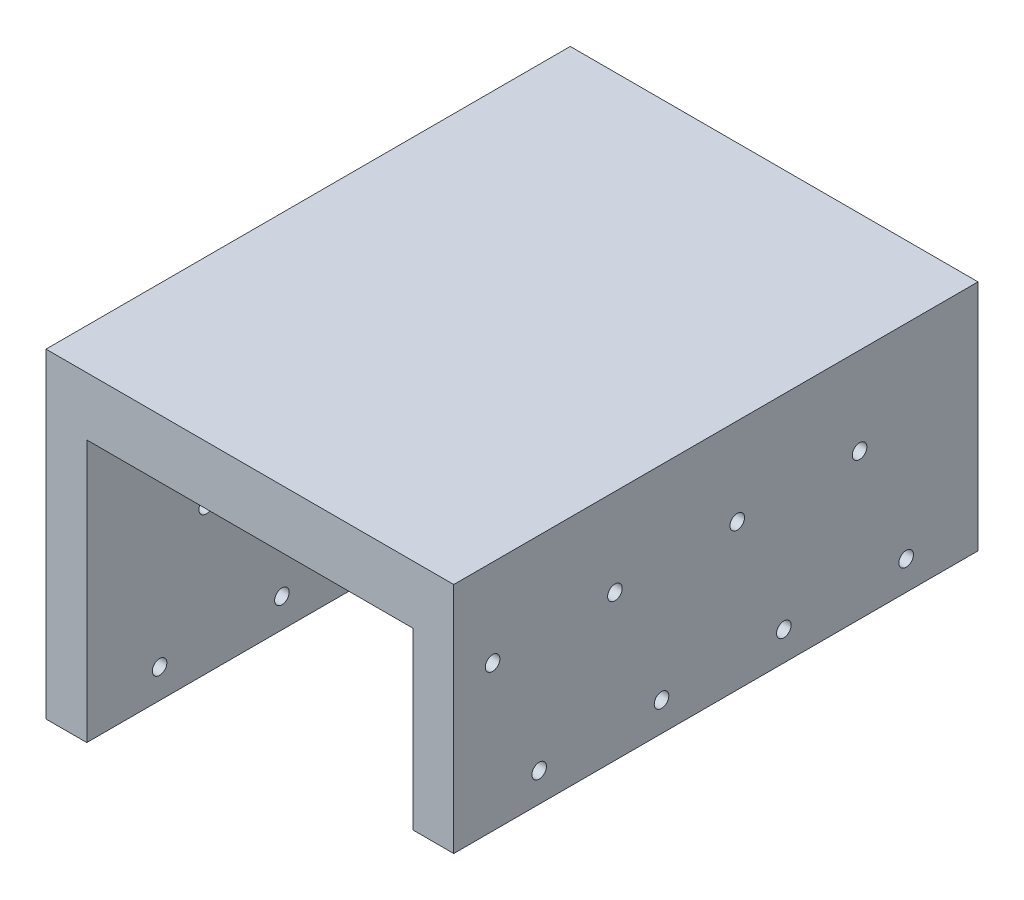
SolidWorks part; units mm, degrees
ref_plane "Front Plane" through (0, 0, 0) normal (0, 0, 1) x (1, 0, 0)
ref_plane "Top Plane" through (0, 0, 0) normal (0, 1, 0) x (1, 0, 0)
ref_plane "Right Plane" through (0, 0, 0) normal (1, 0, 0) x (0, 0, -1)
sketch "Sketch1" plane through (0, 0, 0) normal (0, 0, 1) x (1, 0, 0)
  line L1 (0, 0) -> (70, 0)
  line L2 (0, 0) -> (0, 55)
  line L3 (0, 55) -> (70, 55)
  line L4 (70, 0) -> (70, 55)
  dimension "D1" = 70
  dimension "D2" = 55
extrude "Boss-Extrude1" add sketch "Sketch1" along normal blind 90
sketch "Sketch2" plane through (0, 0, 90) normal (0, 0, 1) x (1, 0, 0)
  line L0 (7, 0) -> (7, 45)
  line L1 (0, 0) -> (70, 0) construction
  line L2 (7, 45) -> (63, 45)
  line L3 (63, 45) -> (63, 15)
  line L4 (60, 0) -> (7, 0)
  line L5 (0, 55) -> (0, 0) construction
  line L6 (70, 0) -> (70, 55) construction
  line L7 (70, 55) -> (0, 55) construction
  line L8 (63, 15) -> (70, 15)
  line L9 (70, 15) -> (70, 0)
  line L10 (70, 0) -> (60, 0)
  dimension "D1" = 7
  dimension "D2" = 7
  dimension "D3" = 10
  dimension "D4" = 15
extrude "Cut-Extrude1" cut sketch "Sketch2" against normal through all both and the other way through all
sketch "Sketch3" plane through (0, 0, 0) normal (-1, 0, 0) x (0, 0, 1)
  line L0 (90, 0) -> (0, 0) construction
  line L1 (0, 55) -> (0, 0) construction
  circle A0 centre (6.5, 25) radius 1.25
  circle A1 centre (14.5, 5) radius 1.25
  circle A2 centre (27.5, 25) radius 1.25
  circle A3 centre (35.5, 5) radius 1.25
  circle A4 centre (48.5, 25) radius 1.25
  circle A5 centre (56.5, 5) radius 1.25
  circle A6 centre (69.5, 25) radius 1.25
  circle A7 centre (77.5, 5) radius 1.25
  point P6 (0, 0)
  point P13 (0, 0)
  point P14 (0, 0)
  point P15 (0, 0)
  point P24 (0, 0)
  dimension "D2" = 2.5
  dimension "D3" = 2.5
  dimension "D7" = 2.5
  dimension "D8" = 2.5
  dimension "D13" = 2.5
  dimension "D14" = 2.5
  dimension "D17" = 2.5
  dimension "D18" = 2.5
  dimension "D1" = 5
  dimension "D4" = 8
  dimension "D5" = 20
  dimension "D6" = 6.5
  dimension "D9" = 8
  dimension "D10" = 20
  dimension "D11" = 5
  dimension "D12" = 13
  dimension "D15" = 8
  dimension "D16" = 20
  dimension "D19" = 8
  dimension "D20" = 20
  dimension "D21" = 13
  dimension "D22" = 5
  dimension "D23" = 5
  dimension "D24" = 13
sketch "Sketch4" plane through (70, 0, 0) normal (1, 0, 0) x (0, 0, -1)
  line L0 (0, 15) -> (-90, 15) construction
  circle A0 centre (-83.3318, 40) radius 1.25
  circle A1 centre (-75.3318, 20) radius 1.25
  circle A2 centre (-62.3318, 40) radius 1.25
  circle A3 centre (-54.3318, 20) radius 1.25
  circle A4 centre (-41.3318, 40) radius 1.25
  circle A5 centre (-33.3318, 20) radius 1.25
  circle A6 centre (-20.3318, 40) radius 1.25
  circle A7 centre (-12.3318, 20) radius 1.25
  point P16 (0, 0)
  point P19 (0, 0)
  dimension "D1" = 2.5
  dimension "D2" = 2.5
  dimension "D5" = 2.5
  dimension "D6" = 2.5
  dimension "D10" = 2.5
  dimension "D11" = 2.5
  dimension "D14" = 2.5
  dimension "D15" = 2.5
  dimension "D3" = 8
  dimension "D4" = 20
  dimension "D7" = 8
  dimension "D8" = 20
  dimension "D9" = 13
  dimension "D12" = 8
  dimension "D13" = 20
  dimension "D16" = 8
  dimension "D17" = 20
  dimension "D18" = 13
  dimension "D19" = 13
  dimension "D20" = 5
  dimension "D21" = 5
  dimension "D22" = 5
  dimension "D23" = 5
extrude "Cut-Extrude2" cut sketch "Sketch3" against normal up to surface (7 mm away) up to face at (7, 22.5, 45)
extrude "Cut-Extrude4" cut sketch "Sketch4" against normal up to surface (7 mm away) up to face at (63, 30, 45)
